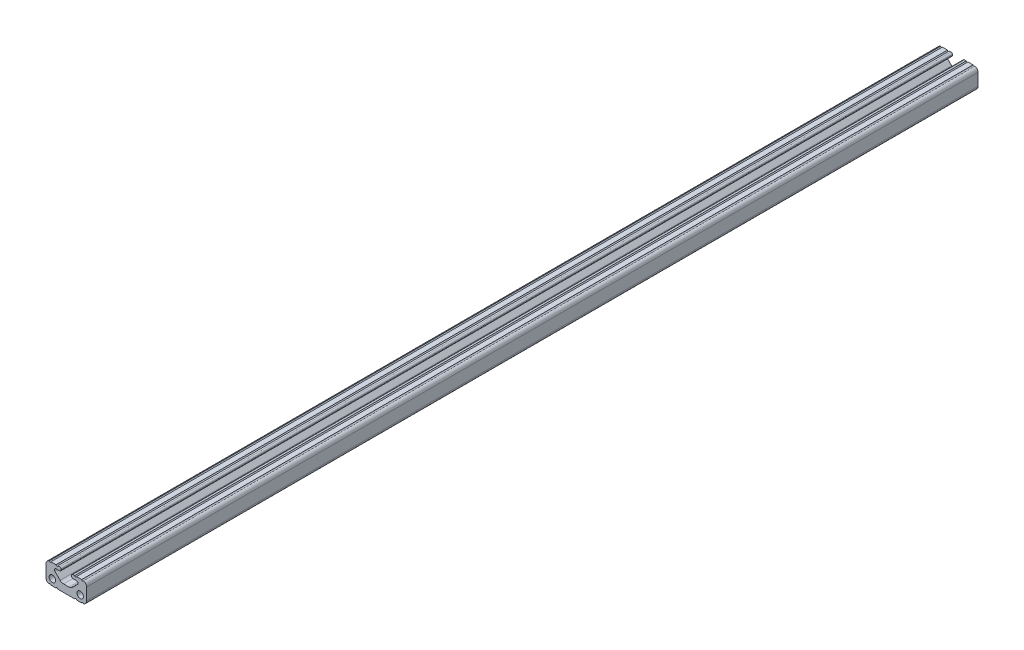
SolidWorks part; units mm, degrees
ref_plane "Front Plane" through (0, 0, 0) normal (0, 0, 1) x (1, 0, 0)
ref_plane "Top Plane" through (0, 0, 0) normal (0, 1, 0) x (1, 0, 0)
ref_plane "Right Plane" through (0, 0, 0) normal (1, 0, 0) x (0, 0, -1)
sketch "Sketch1" plane through (0, 0, 0) normal (0, 0, 1) x (1, 0, 0)
  line L0 (0, 6.35) -> (0, -6.35) construction
  line L1 (0, -6.35) -> (12.7, -6.35)
  line L2 (12.7, -6.35) -> (12.7, 6.35)
  line L3 (12.7, 6.35) -> (3.2512, 6.35)
  line L4 (3.2512, 6.35) -> (3.2512, 4.1402)
  line L5 (3.2512, 4.1402) -> (6.4224, 4.1402)
  line L6 (7.1255, 2.4426) -> (2.9811, -1.7018)
  line L7 (2.9811, -1.7018) -> (0, -1.7018)
  circle A0 centre (8.7249, -2.3876) radius 2.032
  arc A1 (6.4224, 4.1402) -> (7.1255, 2.4426) centre (6.4224, 3.1458) cw
  dimension "Center Hole Diameter" = 4.064
  dimension "D3" = 0.9944
  dimension "Rail Height" = 25.4
  dimension "Rail Width" = 12.7
  dimension "Hole CtoC" = 17.4498
  dimension "D1" = 3.9624
  dimension "T-Slot Width" = 6.5024
  dimension "Thickness" = 2.2098
  dimension "Inner Slot Width" = 14.8336
  dimension "Slot Depth" = 5.842
  dimension "D2" = 45
sketch "Sketch2" plane through (0, 0, 0) normal (1, 0, 0) x (0, 0, -1)
  line L0 (-304.8, -6.35) -> (304.8, -6.35) construction
  line L1 (-279.4, 0) -> (279.4, 0) construction
  dimension "Length" = 609.6
  dimension "D1" = 25.4
sketch "Sketch3" plane through (0, 0, 0) normal (0, 0, 1) x (1, 0, 0)
  line L0 (3.2512, 6.35) -> (3.2512, 4.1402) construction
  line L1 (12.7, 6.35) -> (3.2512, 6.35) construction
  line L2 (3.2512, 4.1402) -> (6.4224, 4.1402) construction
  line L3 (3.2512, 5.3556) -> (3.2512, 5.1346)
  line L4 (12.7, -6.35) -> (12.7, 6.35) construction
  line L5 (0, -6.35) -> (12.7, -6.35) construction
  line L6 (2.9811, -1.7018) -> (0, -1.7018) construction
  line L7 (7.1255, 2.4426) -> (2.9811, -1.7018) construction
  line L8 (0, -1.7018) -> (1.7454, -1.7018)
  line L9 (4.2456, 4.1402) -> (6.4224, 4.1402)
  line L10 (3.8549, -0.828) -> (7.1255, 2.4426)
  line L11 (0, -1.7018) -> (0, -6.35)
  line L12 (0, -6.35) -> (10.16, -6.35)
  line L13 (12.7, -3.81) -> (12.7, 3.81)
  line L14 (4.2456, 6.35) -> (10.16, 6.35)
  arc A0 (3.2512, 5.3556) -> (4.2456, 6.35) centre (4.2456, 5.3556) cw
  arc A1 (3.2512, 5.1346) -> (4.2456, 4.1402) centre (4.2456, 5.1346) ccw
  arc A2 (7.1255, 2.4426) -> (6.4224, 4.1402) centre (6.4224, 3.1458) ccw construction
  arc A3 (10.16, 6.35) -> (12.7, 3.81) centre (10.16, 3.81) cw
  arc A4 (10.16, -6.35) -> (12.7, -3.81) centre (10.16, -3.81) ccw
  arc A5 (7.1255, 2.4426) -> (6.4224, 4.1402) centre (6.4224, 3.1458) ccw
  circle A6 centre (8.7249, -2.3876) radius 2.032 construction
  circle A7 centre (8.7249, -2.3876) radius 2.032
  arc A8 (1.7454, -1.7018) -> (3.8549, -0.828) centre (1.7454, 1.2814) ccw
  dimension "D2" = 2.9832
  dimension "D1" = 2.54
extrude "Boss-Extrude1" add sketch "Sketch3" along normal mid plane 609.6
sketch "Sketch4" plane through (0, 0, 0) normal (0, 0, 1) x (1, 0, 0)
  line L0 (12.7, 6.35) -> (3.2512, 6.35) construction
  line L1 (0, -6.35) -> (12.7, -6.35) construction
  line L2 (10.7569, -2.3876) -> (10.7569, 6.35) construction
  line L3 (6.4224, 3.1458) -> (6.4224, 6.35) construction
  circle A0 centre (5.8699, 6.35) radius 0.5524
  circle A1 centre (10.2045, 6.35) radius 0.5524
  circle A2 centre (5.8699, -6.35) radius 0.5524
  circle A3 centre (10.2045, -6.35) radius 0.5524
  circle A4 centre (8.7249, -2.3876) radius 2.032 construction
  dimension "D1" = 1.1049
extrude "Cut-Extrude1" cut sketch "Sketch4" against normal through all both and the other way through all
mirror "Mirror1" about plane through (0, 0, 0) normal (1, 0, 0) of bodies 135
sketch "Sketch5" plane through (0, 0, 304.8) normal (0, 0, 1) x (1, 0, 0)
  line L16 (9.652, 6.35) -> (6.4224, 6.35)
  line L17 (5.3175, 6.35) -> (4.2456, 6.35)
  line L18 (3.2512, 5.3556) -> (3.2512, 5.1346)
  line L19 (4.2456, 4.1402) -> (6.4224, 4.1402)
  line L20 (7.1255, 2.4426) -> (3.8549, -0.828)
  line L21 (1.7454, -1.7018) -> (-1.7454, -1.7018)
  line L22 (-3.8549, -0.828) -> (-7.1255, 2.4426)
  line L23 (-6.4224, 4.1402) -> (-4.2456, 4.1402)
  line L24 (-3.2512, 5.1346) -> (-3.2512, 5.3556)
  line L25 (-4.2456, 6.35) -> (-5.3175, 6.35)
  line L26 (-6.4224, 6.35) -> (-9.652, 6.35)
  line L27 (-12.7, 3.81) -> (-12.7, -3.81)
  line L28 (-9.652, -6.35) -> (-6.4224, -6.35)
  line L29 (-5.3175, -6.35) -> (5.3175, -6.35)
  line L30 (6.4224, -6.35) -> (9.652, -6.35)
  line L31 (12.7, -3.81) -> (12.7, 3.81)
  line L32 (9.652, 6.35) -> (6.4224, 6.35)
  line L33 (5.3175, 6.35) -> (4.2456, 6.35)
  line L34 (3.2512, 5.3556) -> (3.2512, 5.1346)
  line L35 (4.2456, 4.1402) -> (6.4224, 4.1402)
  line L36 (7.1255, 2.4426) -> (3.8549, -0.828)
  line L37 (1.7454, -1.7018) -> (-1.7454, -1.7018)
  line L38 (-3.8549, -0.828) -> (-7.1255, 2.4426)
  line L39 (-6.4224, 4.1402) -> (-4.2456, 4.1402)
  line L40 (-3.2512, 5.1346) -> (-3.2512, 5.3556)
  line L41 (-4.2456, 6.35) -> (-5.3175, 6.35)
  line L42 (-6.4224, 6.35) -> (-9.652, 6.35)
  line L43 (-12.7, 3.81) -> (-12.7, -3.81)
  line L44 (-9.652, -6.35) -> (-6.4224, -6.35)
  line L45 (-5.3175, -6.35) -> (5.3175, -6.35)
  line L46 (6.4224, -6.35) -> (9.652, -6.35)
  line L47 (12.7, -3.81) -> (12.7, 3.81)
  arc A20 (12.7, 3.81) -> (10.7524, 6.2799) centre (10.16, 3.81) ccw
  arc A21 (9.652, 6.35) -> (10.7524, 6.2799) centre (10.2045, 6.35) ccw
  arc A22 (5.3175, 6.35) -> (6.4224, 6.35) centre (5.8699, 6.35) ccw
  arc A23 (4.2456, 6.35) -> (3.2512, 5.3556) centre (4.2456, 5.3556) ccw
  arc A24 (3.2512, 5.1346) -> (4.2456, 4.1402) centre (4.2456, 5.1346) ccw
  arc A25 (7.1255, 2.4426) -> (6.4224, 4.1402) centre (6.4224, 3.1458) ccw
  arc A26 (1.7454, -1.7018) -> (3.8549, -0.828) centre (1.7454, 1.2814) ccw
  arc A27 (-3.8549, -0.828) -> (-1.7454, -1.7018) centre (-1.7454, 1.2814) ccw
  arc A28 (-6.4224, 4.1402) -> (-7.1255, 2.4426) centre (-6.4224, 3.1458) ccw
  arc A29 (-4.2456, 4.1402) -> (-3.2512, 5.1346) centre (-4.2456, 5.1346) ccw
  arc A30 (-3.2512, 5.3556) -> (-4.2456, 6.35) centre (-4.2456, 5.3556) ccw
  arc A31 (-6.4224, 6.35) -> (-5.3175, 6.35) centre (-5.8699, 6.35) ccw
  arc A32 (-10.7524, 6.2799) -> (-9.652, 6.35) centre (-10.2045, 6.35) ccw
  arc A33 (-10.7524, 6.2799) -> (-12.7, 3.81) centre (-10.16, 3.81) ccw
  arc A34 (-12.7, -3.81) -> (-10.7524, -6.2799) centre (-10.16, -3.81) ccw
  arc A35 (-9.652, -6.35) -> (-10.7524, -6.2799) centre (-10.2045, -6.35) ccw
  arc A36 (-5.3175, -6.35) -> (-6.4224, -6.35) centre (-5.8699, -6.35) ccw
  arc A37 (6.4224, -6.35) -> (5.3175, -6.35) centre (5.8699, -6.35) ccw
  arc A38 (10.7524, -6.2799) -> (9.652, -6.35) centre (10.2045, -6.35) ccw
  arc A39 (10.7524, -6.2799) -> (12.7, -3.81) centre (10.16, -3.81) ccw
  arc A40 (12.7, 3.81) -> (10.7524, 6.2799) centre (10.16, 3.81) ccw
  arc A41 (9.652, 6.35) -> (10.7524, 6.2799) centre (10.2045, 6.35) ccw
  arc A42 (5.3175, 6.35) -> (6.4224, 6.35) centre (5.8699, 6.35) ccw
  arc A43 (4.2456, 6.35) -> (3.2512, 5.3556) centre (4.2456, 5.3556) ccw
  arc A44 (3.2512, 5.1346) -> (4.2456, 4.1402) centre (4.2456, 5.1346) ccw
  arc A45 (7.1255, 2.4426) -> (6.4224, 4.1402) centre (6.4224, 3.1458) ccw
  arc A46 (1.7454, -1.7018) -> (3.8549, -0.828) centre (1.7454, 1.2814) ccw
  arc A47 (-3.8549, -0.828) -> (-1.7454, -1.7018) centre (-1.7454, 1.2814) ccw
  arc A48 (-6.4224, 4.1402) -> (-7.1255, 2.4426) centre (-6.4224, 3.1458) ccw
  arc A49 (-4.2456, 4.1402) -> (-3.2512, 5.1346) centre (-4.2456, 5.1346) ccw
  arc A50 (-3.2512, 5.3556) -> (-4.2456, 6.35) centre (-4.2456, 5.3556) ccw
  arc A51 (-6.4224, 6.35) -> (-5.3175, 6.35) centre (-5.8699, 6.35) ccw
  arc A52 (-10.7524, 6.2799) -> (-9.652, 6.35) centre (-10.2045, 6.35) ccw
  arc A53 (-10.7524, 6.2799) -> (-12.7, 3.81) centre (-10.16, 3.81) ccw
  arc A54 (-12.7, -3.81) -> (-10.7524, -6.2799) centre (-10.16, -3.81) ccw
  arc A55 (-9.652, -6.35) -> (-10.7524, -6.2799) centre (-10.2045, -6.35) ccw
  arc A56 (-5.3175, -6.35) -> (-6.4224, -6.35) centre (-5.8699, -6.35) ccw
  arc A57 (6.4224, -6.35) -> (5.3175, -6.35) centre (5.8699, -6.35) ccw
  arc A58 (10.7524, -6.2799) -> (9.652, -6.35) centre (10.2045, -6.35) ccw
  arc A59 (10.7524, -6.2799) -> (12.7, -3.81) centre (10.16, -3.81) ccw
  dimension "D1" = 0
extrude "Cut-Extrude2" cut sketch "Sketch5" against normal offset from surface (50.8 mm away) 558.8
equation "\"D3@Sketch1\"=\"Thickness@Sketch1\"*0.45"
equation "\"D1@Sketch3\"=\"Rail Width@Sketch1\"*0.2"
equation "\"D2@Sketch3\"=\"D3@Sketch1\"*3"
equation "\"D1@Boss-Extrude1\"=\"length@sketch2\""
equation "\"D1@Sketch4\"=\"Thickness@Sketch1\"*0.5"
